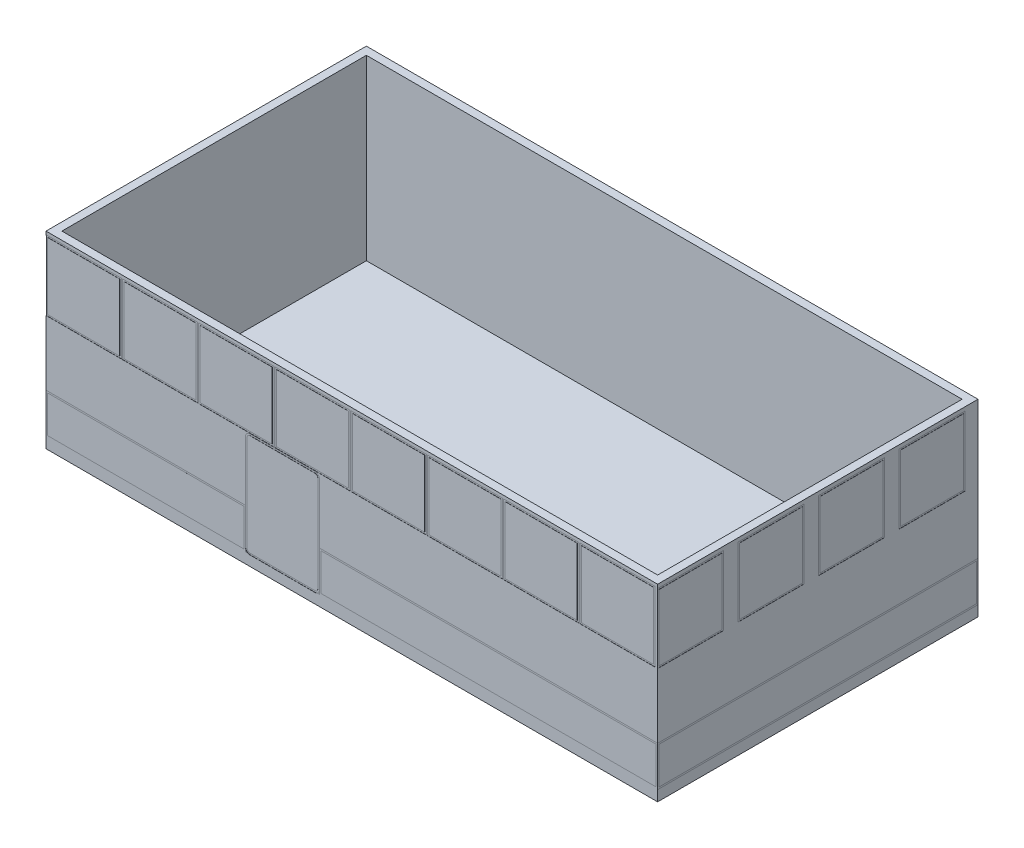
SolidWorks part; units mm, degrees
ref_plane "Alzado" through (0, 0, 0) normal (0, 0, 1) x (1, 0, 0)
ref_plane "Planta" through (0, 0, 0) normal (0, 1, 0) x (1, 0, 0)
ref_plane "Vista lateral" through (0, 0, 0) normal (1, 0, 0) x (0, 0, -1)
sketch "Croquis1" plane through (0, 0, 0) normal (0, 1, 0) x (1, 0, 0)
  line L0 (-5775, 3025) -> (-5775, -3025)
  line L1 (-5625, 2875) -> (5625, 2875)
  line L2 (-5625, 2875) -> (-5625, -2875)
  line L3 (-5625, -2875) -> (5625, -2875)
  line L4 (5625, 2875) -> (5625, -2875)
  line L5 (-5625, 2875) -> (5625, -2875) construction
  line L6 (-5625, -2875) -> (5625, 2875) construction
  line L7 (-5775, -3025) -> (5775, -3025)
  line L8 (5775, 3025) -> (5775, -3025)
  line L9 (-5775, 3025) -> (5775, 3025)
  point P0 (0, 0)
  dimension "D1" = 11250
  dimension "D2" = 5750
  dimension "D3" = 150
extrude "Saliente-Extruir1" add sketch "Croquis1" along normal blind 3360
sketch "Croquis2" plane through (0, 0, 0) normal (0, -1, 0) x (1, 0, 0)
  line L1 (-5775, 3025) -> (5775, 3025)
  line L2 (-5775, 3025) -> (-5775, -3025)
  line L3 (-5775, -3025) -> (5775, -3025)
  line L4 (5775, 3025) -> (5775, -3025)
  line L5 (-5775, 3025) -> (5775, -3025) construction
  line L6 (-5775, -3025) -> (5775, 3025) construction
  point P0 (0, 0)
extrude "Saliente-Extruir2" add sketch "Croquis2" along normal blind 200
sketch "Croquis3" plane through (0, 0, 3025) normal (0, 0, 1) x (1, 0, 0)
  line L0 (-5775, -200) -> (-5775, 1980) construction
  line L1 (-5775, 3360) -> (-5775, -200) construction
  line L2 (-5775, 1980) -> (5775, 1980) construction
  line L3 (-5775, 3300.8637) -> (-4353.7549, 3300.8637)
  line L4 (-5775, 3300.8637) -> (-5775, 1980)
  line L5 (-5775, 1980) -> (-4353.7549, 1980)
  line L6 (-4353.7549, 3300.8637) -> (-4353.7549, 1980)
  line L7 (-5775, 3300.8637) -> (-4353.7549, 1980) construction
  line L8 (-5775, 1980) -> (-4353.7549, 3300.8637) construction
  line L9 (5775, 3360) -> (5775, -200) construction
  line L10 (-4383.7549, 3270.8637) -> (-4383.7549, 2010)
  line L11 (-5745, 2010) -> (-4383.7549, 2010)
  line L12 (-5745, 3270.8637) -> (-5745, 2010)
  line L13 (-5745, 3270.8637) -> (-4383.7549, 3270.8637)
  point P5 (-5064.3774, 2640.4318)
  dimension "D1" = 2180
  dimension "D2" = 30
extrude "Cortar-Extruir1" cut sketch "Croquis3" against normal blind 3
pattern_linear "MatrizL1" count 8 spacing 1440 along (1, 0, 0) of "Cortar-Extruir1"
sketch "Croquis4" plane through (5775, 0, 0) normal (1, 0, 0) x (0, 0, -1)
  line L0 (-3025, -200) -> (-3025, 1980) construction
  line L1 (-3025, 3360) -> (-3025, -200) construction
  line L2 (-2995, 2010) -> (-1810.8215, 2010)
  line L3 (-3025, 3289.3616) -> (-1780.8215, 3289.3616)
  line L4 (-3025, 3289.3616) -> (-3025, 1980)
  line L5 (-3025, 1980) -> (-1780.8215, 1980)
  line L6 (-1780.8215, 3289.3616) -> (-1780.8215, 1980)
  line L7 (-3025, 3289.3616) -> (-1780.8215, 1980) construction
  line L8 (-3025, 1980) -> (-1780.8215, 3289.3616) construction
  line L9 (-1810.8215, 3259.3616) -> (-1810.8215, 2010)
  line L10 (-2995, 3259.3616) -> (-1810.8215, 3259.3616)
  line L11 (-2995, 3259.3616) -> (-2995, 2010)
  point P5 (-2402.9108, 2634.6808)
  dimension "D1" = 2180
  dimension "D2" = 30
extrude "Cortar-Extruir2" cut sketch "Croquis4" against normal blind 3
pattern_linear "MatrizL2" count 4 spacing 1520 along (0, 0, -1) of "Cortar-Extruir2"
sketch "Croquis5" plane through (-5775, 0, 0) normal (-1, 0, 0) x (0, 0, 1)
  line L0 (2995, 3259.3616) -> (1810.8215, 3259.3616)
  line L1 (1810.8215, 3259.3616) -> (1810.8215, 2010)
  line L2 (1810.8215, 2010) -> (2995, 2010)
  line L3 (2995, 2010) -> (2995, 3259.3616)
  line L4 (1780.8215, 3289.3616) -> (1780.8215, 1980)
  line L5 (1780.8215, 1980) -> (3025, 1980)
  line L6 (3025, 1980) -> (3025, 3289.3616)
  line L7 (3025, 3289.3616) -> (1780.8215, 3289.3616)
  dimension "D1" = 30
extrude "Cortar-Extruir3" cut sketch "Croquis5" against normal blind 3
pattern_linear "MatrizL3" count 4 spacing 1520 along (0, 0, -1) of "Cortar-Extruir3"
sketch "Croquis6" plane through (0, 0, 3025) normal (0, 0, 1) x (1, 0, 0)
  line L0 (0, 0) -> (-3847.4966, 0) construction
  line L1 (-1920.2934, 1969.3183) -> (-700.2934, 1969.3183)
  line L2 (-2010.2934, 1879.3183) -> (-2010.2934, 79.3183)
  line L3 (-1920.2934, -10.6817) -> (-700.2934, -10.6817)
  line L4 (-610.2934, 1879.3183) -> (-610.2934, 79.3183)
  line L5 (-2010.2934, 1969.3183) -> (-610.2934, -10.6817) construction
  line L6 (-2010.2934, -10.6817) -> (-610.2934, 1969.3183) construction
  line L7 (-1980.2934, 1879.3183) -> (-1980.2934, 79.3183)
  line L8 (-1920.2934, 19.3183) -> (-700.2934, 19.3183)
  line L9 (-640.2934, 1879.3183) -> (-640.2934, 79.3183)
  line L10 (-1920.2934, 1939.3183) -> (-700.2934, 1939.3183)
  arc A0 (-2010.2934, 79.3183) -> (-1920.2934, -10.6817) centre (-1920.2934, 79.3183) ccw
  arc A1 (-700.2934, -10.6817) -> (-610.2934, 79.3183) centre (-700.2934, 79.3183) ccw
  arc A2 (-700.2934, 1969.3183) -> (-610.2934, 1879.3183) centre (-700.2934, 1879.3183) cw
  arc A3 (-1920.2934, 1969.3183) -> (-2010.2934, 1879.3183) centre (-1920.2934, 1879.3183) ccw
  arc A4 (-2010.2934, 79.3183) -> (-1920.2934, -10.6817) centre (-1920.2934, 79.3183) ccw
  arc A5 (-1980.2934, 79.3183) -> (-1920.2934, 19.3183) centre (-1920.2934, 79.3183) ccw
  arc A6 (-700.2934, 19.3183) -> (-640.2934, 79.3183) centre (-700.2934, 79.3183) ccw
  arc A7 (-700.2934, 1939.3183) -> (-640.2934, 1879.3183) centre (-700.2934, 1879.3183) cw
  arc A8 (-1920.2934, 1939.3183) -> (-1980.2934, 1879.3183) centre (-1920.2934, 1879.3183) ccw
  point P0 (-1310.2934, 979.3183)
  dimension "D3" = 90
  dimension "D4" = 90
  dimension "D1" = 1980
  dimension "D2" = 1400
  dimension "D5" = 30
extrude "Cortar-Extruir4" cut sketch "Croquis6" against normal blind 3 contours L1 A3 L2 A0 L3 A1 L4 A2 A8 L10 A7 L9 A6 L8 A5 L7
sketch "Croquis7" plane through (0, 0, 3025) normal (0, 0, 1) x (1, 0, 0)
  line L0 (-5775, -200) -> (-5775, 0)
  line L1 (-5775, 1980) -> (-5775, -200) construction
  line L2 (-5775, 0) -> (5775, 0)
  line L3 (5775, 1980) -> (5775, -200) construction
  line L4 (5775, 0) -> (5775, -200)
  line L5 (5775, -200) -> (-5775, -200)
extrude "Cortar-Extruir5" cut sketch "Croquis7" against normal blind 0.011
sketch "Croquis8" plane through (5775, 0, 0) normal (1, 0, 0) x (0, 0, -1)
  line L0 (-3024.989, -200) -> (-3025, 0)
  line L1 (-3025, 0) -> (3025, 0)
  line L2 (3025, 3360) -> (3025, -200) construction
  line L3 (3025, 0) -> (3025, -200)
  line L4 (3025, -200) -> (-3024.989, -200)
extrude "Cortar-Extruir6" cut sketch "Croquis8" against normal blind 0.011
sketch "Croquis9" plane through (0, 0, -3025) normal (0, 0, -1) x (-1, 0, 0)
  line L0 (-5774.989, -200) -> (-5774.989, 0)
  line L1 (-5774.989, 0) -> (5775, 0)
  line L2 (5775, 0) -> (5775, -200)
  line L3 (5775, -200) -> (-5774.989, -200)
extrude "Cortar-Extruir7" cut sketch "Croquis9" against normal blind 0.011
sketch "Croquis10" plane through (-5775, 0, 0) normal (-1, 0, 0) x (0, 0, 1)
  line L0 (-3024.989, -200) -> (-3024.989, 0)
  line L1 (-3024.989, 0) -> (3024.989, -10.6817)
  line L2 (3024.989, -10.6817) -> (3024.989, -200)
  line L3 (3024.989, -200) -> (-3024.989, -200)
extrude "Cortar-Extruir8" cut sketch "Croquis10" against normal blind 0.011
sketch "Croquis11" plane through (0, 0, -3025) normal (0, 0, -1) x (-1, 0, 0)
  line L0 (4383.7549, 3270.8637) -> (4383.7549, 2010)
  line L1 (4383.7549, 2010) -> (5745, 2010)
  line L2 (5745, 2010) -> (5745, 3270.8637)
  line L3 (5745, 3270.8637) -> (4383.7549, 3270.8637)
  line L4 (4353.7549, 3300.8637) -> (4353.7549, 1980)
  line L5 (4353.7549, 1980) -> (5775, 1980)
  line L6 (5775, 1980) -> (5775, 3300.8637)
  line L7 (5775, 3300.8637) -> (4353.7549, 3300.8637)
  dimension "D1" = 30
extrude "Cortar-Extruir9" cut sketch "Croquis11" against normal blind 0.011
pattern_linear "MatrizL4" count 8 spacing 1440 along (1, 0, 0) of "Cortar-Extruir9"
sketch "Croquis12" plane through (-5775, 0, 0) normal (-1, 0, 0) x (0, 0, 1)
  line L0 (-2087.8268, -1.6546) -> (-2087.8268, 1954.1197)
  line L1 (3024.989, -10.6817) -> (-3024.989, 0) construction
  line L2 (-2087.8268, 1954.1197) -> (1430.8499, 1954.1197)
  line L3 (1430.8499, 1954.1197) -> (1430.8499, -7.8671)
  line L4 (3024.989, -10.6817) -> (-3024.989, 0) construction
  line L5 (1430.8499, -7.8671) -> (-2087.8268, -1.6546)
  line L6 (-2057.8268, 28.2924) -> (-2057.8268, 1924.1197)
  line L7 (-2057.8268, 1924.1197) -> (1400.8499, 1924.1197)
  line L8 (1400.8499, 1924.1197) -> (1400.8499, 22.1859)
  line L9 (1400.8499, 22.1859) -> (-2057.8268, 28.2924)
  dimension "D1" = 30
extrude "Cortar-Extruir10" cut sketch "Croquis12" against normal blind 0.011
sketch "Croquis13" plane through (0, 0, 3025) normal (0, 0, 1) x (1, 0, 0)
  line L0 (-5775, 758.5264) -> (-2010.2934, 758.5264)
  line L1 (-5775, 1980) -> (-5775, 0) construction
  line L2 (-2010.2934, 1879.3183) -> (-2010.2934, 79.3183) construction
  line L3 (-2010.2934, 758.5264) -> (-2010.2934, 0)
  line L4 (-1962.8212, 0) -> (-5775, 0) construction
  line L5 (-5775, 758.5264) -> (-5775, 0)
  line L6 (-5775, 0) -> (-2010.2934, 0)
  line L7 (5775, 0) -> (5775, 758.5264)
  line L8 (5775, 1980) -> (5775, 0) construction
  line L9 (5775, 758.5264) -> (-610.2934, 758.5264)
  line L10 (-610.2934, 1879.3183) -> (-610.2934, 79.3183) construction
  line L11 (-610.2934, 758.5264) -> (-610.2934, 0)
  line L12 (5774.989, 0) -> (-657.7656, 0) construction
  line L13 (-610.2934, 0) -> (5775, 0)
  line L14 (-5745, 728.5264) -> (-5745, 30)
  line L15 (-5745, 30) -> (-2040.2934, 30)
  line L16 (-2040.2934, 728.5264) -> (-2040.2934, 30)
  line L17 (-5745, 728.5264) -> (-2040.2934, 728.5264)
  line L18 (5745, 728.5264) -> (-580.2934, 728.5264)
  line L19 (-580.2934, 728.5264) -> (-580.2934, 30)
  line L20 (-580.2934, 30) -> (5745, 30)
  line L21 (5745, 30) -> (5745, 728.5264)
  dimension "D1" = 30
extrude "Cortar-Extruir13" cut sketch "Croquis13" against normal blind 0.011
sketch "Croquis14" plane through (5775, 0, 0) normal (1, 0, 0) x (0, 0, -1)
  line L0 (-3024.989, 758.5264) -> (3025, 758.5264)
  line L1 (3025, 3360) -> (3025, 0) construction
  line L2 (3025, 758.5264) -> (3024.989, 0)
  line L3 (3024.989, 0) -> (-3024.989, 0)
  line L4 (-3024.989, 0) -> (-3024.989, 758.5264)
  line L5 (-2994.989, 30) -> (-2994.989, 728.5264)
  line L6 (-2994.989, 728.5264) -> (2994.9996, 728.5264)
  line L7 (2994.9996, 728.5264) -> (2994.9894, 30)
  line L8 (2994.9894, 30) -> (-2994.989, 30)
  dimension "D1" = 30
extrude "Cortar-Extruir14" cut sketch "Croquis14" against normal blind 0.0011
sketch "Croquis16" plane through (0, 0, -3025) normal (0, 0, -1) x (-1, 0, 0)
  line L0 (-5775, 0) -> (5774.989, 0)
  line L1 (-5774.9995, 758.5264) -> (-5775, 0)
  line L2 (-5774.9995, 758.5264) -> (5775, 758.5264)
  line L3 (5775, 758.5264) -> (5774.989, 0)
extrude "Saliente-Extruir3" add sketch "Croquis16" along normal blind 0.0011
